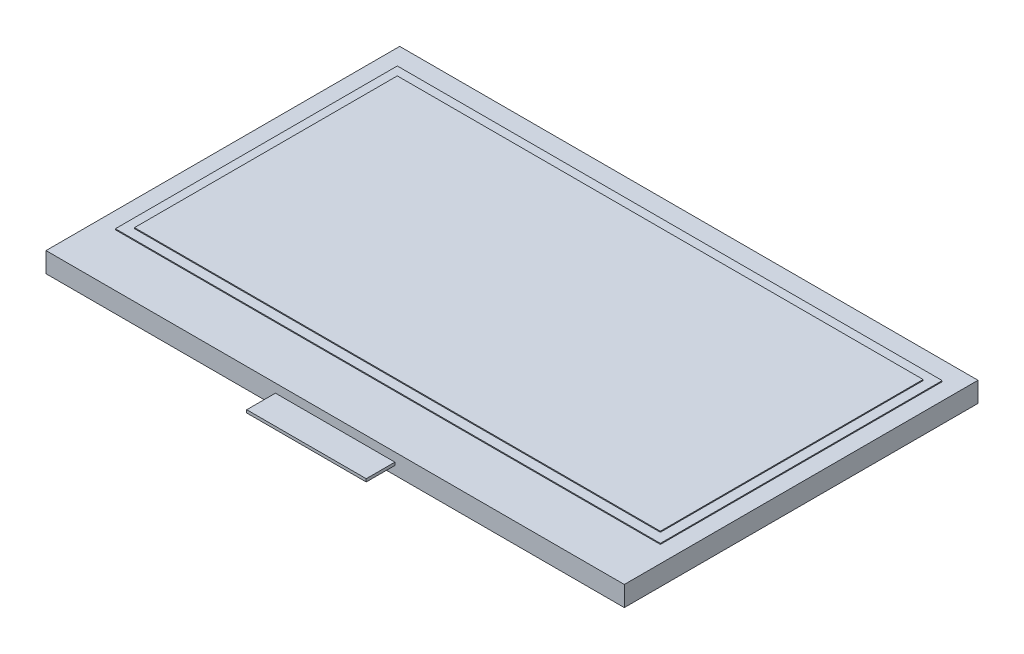
SolidWorks part; units mm, degrees
ref_plane "前视基准面" through (0, 0, 0) normal (0, 0, 1) x (1, 0, 0)
ref_plane "上视基准面" through (0, 0, 0) normal (0, 1, 0) x (1, 0, 0)
ref_plane "右视基准面" through (0, 0, 0) normal (1, 0, 0) x (0, 0, -1)
sketch "草图1" plane through (0, 0, 0) normal (0, 1, 0) x (1, 0, 0)
  line L1 (30.25, -18.5) -> (-30.25, -18.5)
  line L2 (30.25, -18.5) -> (30.25, 18.5)
  line L3 (30.25, 18.5) -> (-30.25, 18.5)
  line L4 (-30.25, -18.5) -> (-30.25, 18.5)
  line L5 (30.25, -18.5) -> (-30.25, 18.5) construction
  line L6 (30.25, 18.5) -> (-30.25, -18.5) construction
  point P0 (0, 0)
  dimension "D1" = 60.5
  dimension "D2" = 37
extrude "凸台-拉伸1" add sketch "草图1" along normal blind 2.1
sketch "草图2" plane through (0, 2.1, 0) normal (0, 1, 0) x (1, 0, 0)
  line L0 (-30.25, 18.5) -> (-30.25, -18.5) construction
  line L1 (-28.5, 16.5) -> (28.51, 16.5)
  line L2 (-28.5, 16.5) -> (-28.5, -12.99)
  line L3 (-28.5, -12.99) -> (28.51, -12.99)
  line L4 (28.51, 16.5) -> (28.51, -12.99)
  line L5 (30.25, 18.5) -> (-30.25, 18.5) construction
  dimension "D1" = 1.75
  dimension "D2" = 2
  dimension "D3" = 57.01
  dimension "D4" = 29.49
extrude "凸台-拉伸2" add sketch "草图2" along normal blind 0.1
sketch "草图5" plane through (0, 2.2, 0) normal (0, 1, 0) x (1, 0, 0)
  line L8 (-27.5, -11.99) -> (27.51, -11.99)
  line L9 (27.51, -11.99) -> (27.51, 15.5)
  line L10 (27.51, 15.5) -> (-27.5, 15.5)
  line L11 (-27.5, 15.5) -> (-27.5, -11.99)
  line L12 (-27.5, -11.99) -> (27.51, -11.99)
  line L13 (27.51, -11.99) -> (27.51, 15.5)
  line L14 (27.51, 15.5) -> (-27.5, 15.5)
  line L15 (-27.5, 15.5) -> (-27.5, -11.99)
  dimension "D1" = 1
extrude "凸台-拉伸4" add sketch "草图5" along normal blind 0.1
sketch "草图3" plane through (0, 0, 18.5) normal (0, 0, 1) x (1, 0, 0)
  line L0 (-30.25, 2.1) -> (-30.25, 0) construction
  line L1 (-6.25, 1.1819) -> (6.25, 1.1819)
  line L2 (-6.25, 1.1819) -> (-6.25, 0.8819)
  line L3 (-6.25, 0.8819) -> (6.25, 0.8819)
  line L4 (6.25, 1.1819) -> (6.25, 0.8819)
  dimension "D1" = 24
  dimension "D2" = 12.5
  dimension "D3" = 0.3
extrude "凸台-拉伸3" add sketch "草图3" along normal blind 3
